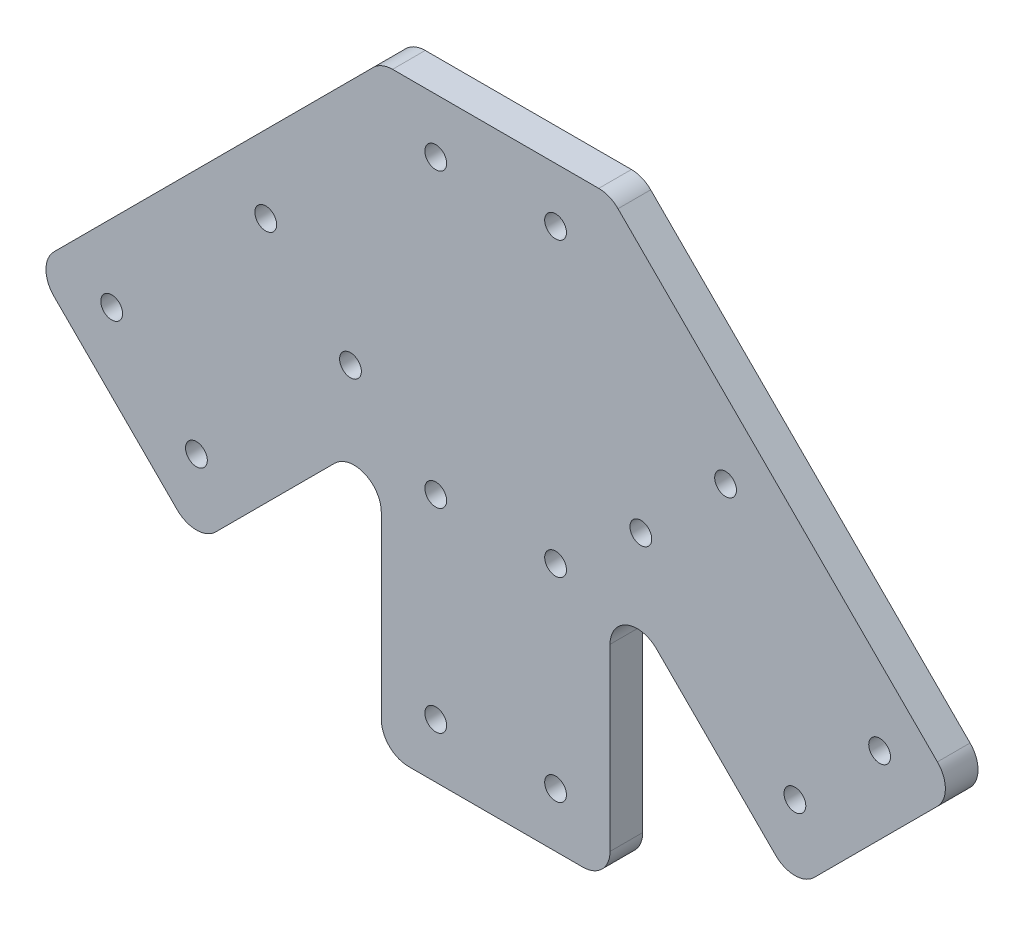
SolidWorks part; units mm, degrees
ref_plane "Спереди" through (0, 0, 0) normal (0, 0, 1) x (1, 0, 0)
ref_plane "Сверху" through (0, 0, 0) normal (0, 1, 0) x (1, 0, 0)
ref_plane "Справа" through (0, 0, 0) normal (1, 0, 0) x (0, 0, -1)
sketch "Эскиз1" plane through (0, 0, 0) normal (0, 0, 1) x (1, 0, 0)
  line L0 (-16, -50) -> (16, -50)
  line L1 (21, -45) -> (21, -12.0711)
  line L2 (29.5355, -8.5355) -> (51.4056, -30.4056)
  line L3 (58.4767, -30.4056) -> (81.1041, -7.7782)
  line L4 (81.1041, -0.7071) -> (22.4645, 57.9325)
  line L5 (18.9289, 59.397) -> (-18.9289, 59.397)
  line L10 (0, -50) -> (0, 59.397) construction
  line L11 (-21, 0) -> (21, 0) construction
  line L12 (-81.1041, -0.7071) -> (-22.4645, 57.9325)
  line L13 (-58.4767, -30.4056) -> (-81.1041, -7.7782)
  line L14 (-29.5355, -8.5355) -> (-51.4056, -30.4056)
  line L15 (-21, -45) -> (-21, -12.0711)
  line L16 (-70.4975, -4.2426) -> (-42.2132, 24.0416) construction
  line L17 (-54.9411, -19.799) -> (-26.6569, 8.4853) construction
  line L18 (-42.2132, 24.0416) -> (-26.6569, 8.4853) construction
  line L19 (-11, 49.397) -> (-11, -40) construction
  arc A0 (-21, -45) -> (-16, -50) centre (-16, -45) ccw
  arc A1 (16, -50) -> (21, -45) centre (16, -45) ccw
  arc A2 (81.1041, -7.7782) -> (81.1041, -0.7071) centre (77.5685, -4.2426) ccw
  arc A3 (51.4056, -30.4056) -> (58.4767, -30.4056) centre (54.9411, -26.8701) ccw
  arc A4 (-58.4767, -30.4056) -> (-51.4056, -30.4056) centre (-54.9411, -26.8701) ccw
  arc A5 (-81.1041, -0.7071) -> (-81.1041, -7.7782) centre (-77.5685, -4.2426) ccw
  arc A6 (-22.4645, 57.9325) -> (-18.9289, 59.397) centre (-18.9289, 54.397) cw
  arc A7 (22.4645, 57.9325) -> (18.9289, 59.397) centre (18.9289, 54.397) ccw
  arc A8 (21, -12.0711) -> (29.5355, -8.5355) centre (26, -12.0711) cw
  arc A9 (-29.5355, -8.5355) -> (-21, -12.0711) centre (-26, -12.0711) cw
  circle A10 centre (-70.4975, -4.2426) radius 2
  circle A11 centre (-54.9411, -19.799) radius 2
  circle A12 centre (-42.2132, 24.0416) radius 2
  circle A13 centre (-26.6569, 8.4853) radius 2
  circle A14 centre (-11, -40) radius 2
  circle A16 centre (-11, 49.397) radius 2
  circle A18 centre (-11, -4.2426) radius 2
  circle A19 centre (11, -40) radius 2
  circle A20 centre (11, -4.2426) radius 2
  circle A21 centre (26.6569, 8.4853) radius 2
  circle A22 centre (54.9411, -19.799) radius 2
  circle A23 centre (70.4975, -4.2426) radius 2
  circle A24 centre (42.2132, 24.0416) radius 2
  circle A25 centre (11, 49.397) radius 2
  point P7 (0, 0)
  point P16 (-21, -50)
  point P19 (21, -50)
  point P22 (84.6396, -4.2426)
  point P25 (54.9411, -33.9411)
  point P28 (-54.9411, -33.9411)
  point P31 (-84.6396, -4.2426)
  point P34 (-21, 59.397)
  point P37 (21, 59.397)
  dimension "D6" = 5
  dimension "D7" = 4
  dimension "D8" = 10
  dimension "D9" = 10
  dimension "D10" = 10
  dimension "D11" = 10
  dimension "D13" = 10
  dimension "D14" = 10
  dimension "D15" = 10
  dimension "D1" = 42
  dimension "D2" = 50
  dimension "D3" = 42
  dimension "D4" = 45
  dimension "D5" = 90
  dimension "D12" = 40
extrude "Бобышка-Вытянуть1" add sketch "Эскиз1" along normal blind 6
